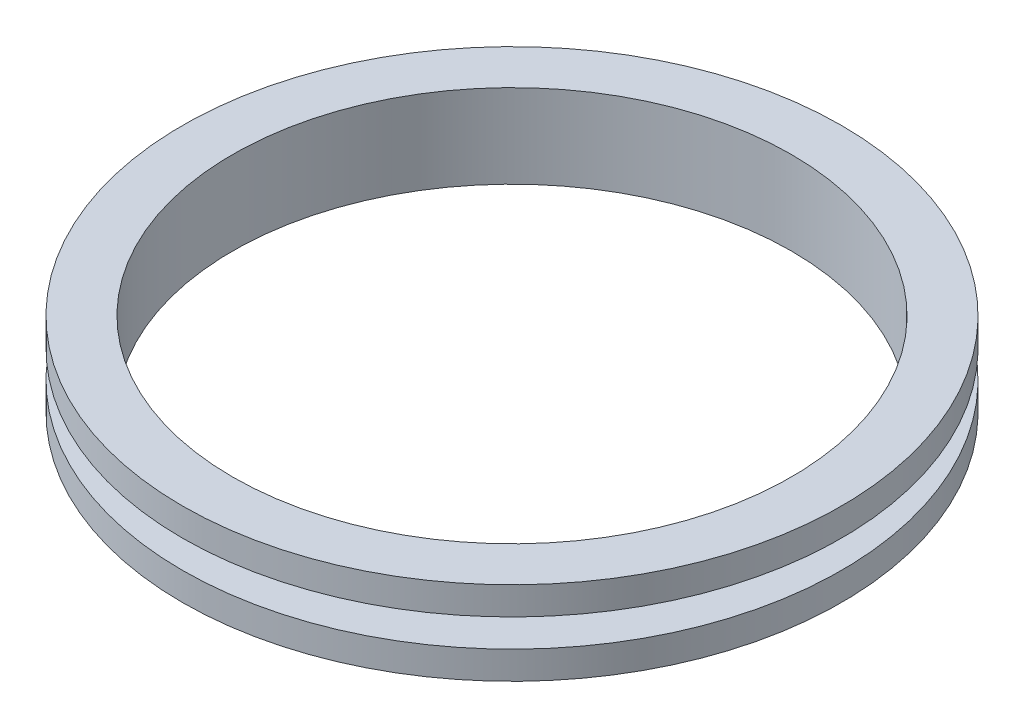
SolidWorks part; units mm, degrees
ref_plane "Front Plane" through (0, 0, 0) normal (0, 0, 1) x (1, 0, 0)
ref_plane "Top Plane" through (0, 0, 0) normal (0, 1, 0) x (1, 0, 0)
ref_plane "Right Plane" through (0, 0, 0) normal (1, 0, 0) x (0, 0, -1)
sketch "Sketch1" plane through (0, 0, 0) normal (0, 1, 0) x (1, 0, 0)
  circle A0 centre (0, 0) radius 25.019
  dimension "D1" = 50.038
extrude "Boss-Extrude1" add sketch "Sketch1" along normal blind 2.1167
sketch "Sketch2" plane through (0, 2.1167, 0) normal (0, 1, 0) x (1, 0, 0)
  circle A0 centre (0, 0) radius 21.59
  dimension "D1" = 43.18
extrude "Boss-Extrude2" add sketch "Sketch2" along normal blind 2.1167
sketch "Sketch3" plane through (0, 4.2333, 0) normal (0, 1, 0) x (1, 0, 0)
  circle A0 centre (0, 0) radius 25.019
  dimension "D1" = 50.038
extrude "Boss-Extrude3" add sketch "Sketch3" along normal blind 2.1167
sketch "Sketch4" plane through (0, 6.35, 0) normal (0, 1, 0) x (1, 0, 0)
  circle A0 centre (0, 0) radius 3.175
  dimension "D1" = 6.35
sketch "Sketch5" plane through (0, 6.35, 0) normal (0, 1, 0) x (1, 0, 0)
  circle A0 centre (0, 0) radius 21.209
  dimension "D1" = 42.418
extrude "Cut-Extrude1" cut sketch "Sketch5" against normal through all
